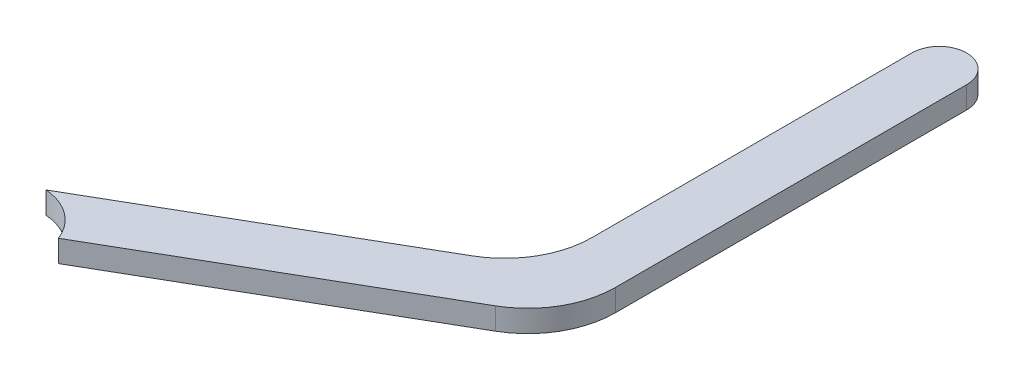
SolidWorks part; units mm, degrees
material "Acrylic (Medium-high impact)"
ref_plane "Front Plane" through (0, 0, 0) normal (0, 0, 1) x (1, 0, 0)
ref_plane "Top Plane" through (0, 0, 0) normal (0, 1, 0) x (1, 0, 0)
ref_plane "Right Plane" through (0, 0, 0) normal (1, 0, 0) x (0, 0, -1)
sketch "Sketch1" plane through (0, 0, 0) normal (0, 1, 0) x (1, 0, 0)
  line L0 (0, 0) -> (-94.8623, -54.7688) construction
  line L1 (0, 0) -> (0, 111.6203) construction
  line L3 (7.9375, 111.6203) -> (7.9375, -4.5827)
  line L4 (-90.8935, -61.6428) -> (7.9375, -4.5827)
  line L5 (-98.831, -47.8947) -> (-90.8935, -61.6428) construction
  line L6 (-98.831, -47.8947) -> (-7.9375, 4.5827)
  line L7 (-7.9375, 111.6203) -> (-7.9375, 4.5827)
  line L9 (-7.9375, 111.6203) -> (7.9375, 111.6203) construction
  arc A0 (-7.9375, 111.6203) -> (7.9375, 111.6203) centre (0, 111.6203) cw
  arc A2 (-98.831, -47.8947) -> (-90.8935, -61.6428) centre (-94.8623, -54.7688) ccw
  point P14 (-94.8623, -54.7688)
  point P18 (0, 0)
  point P22 (0, 111.6203)
  dimension "D1" = 111.6203
  dimension "D2" = 60
  dimension "D3" = 109.5375
  dimension "D4" = 15.875
extrude "Boss-Extrude1" add sketch "Sketch1" along normal blind 6.35
ref_plane "Plane1" through (0, 0, 0) normal (0.5, 0, 0.866) x (0.866, 0, -0.5)
sketch "Sketch2" plane through (0, 6.35, 0) normal (0, 1, 0) x (1, 0, 0)
  line L0 (-90.8935, -61.6428) -> (7.9375, -4.5827) construction
  line L1 (-84.9318, -58.2009) -> (0, -9.1654) construction
  line L2 (-98.831, -47.8947) -> (-15.875, 0) construction
  line L3 (-84.9318, -58.2009) -> (-90.8935, -61.6428)
  line L4 (-7.9375, 4.5827) -> (-98.831, -47.8947) construction
  line L5 (-90.8935, -61.6428) -> (7.9375, -4.5827) construction
  arc A1 (-98.831, -47.8947) -> (-90.8935, -61.6428) centre (-94.8623, -54.7688) ccw construction
  arc A2 (-98.831, -47.8947) -> (-84.9318, -58.2009) centre (-100.0343, -64.043) cw
  arc A3 (-98.831, -47.8947) -> (-90.8935, -61.6428) centre (-94.8623, -54.7688) ccw
  point P2 (-101.7363, -58.7375)
  line M4 (-90.8935, -61.6428) -> (7.9375, -4.5827)
  arc M11 (-98.831, -47.8947) -> (-90.8935, -61.6428) centre (-94.8623, -54.7688) ccw
  dimension "D1" = 16.1931
  dimension "D2" = 16.8045
extrude "Cut-Extrude1" cut sketch "Sketch2" against normal through all contours A2 M11 M4
fillet "Fillet1" radius 25.4 2 edges at (7.9375, 3.175, 4.5827) (-7.9375, 3.175, -4.5827)
sketch "Sketch3" plane through (0, 6.35, 0) normal (0, 1, 0) x (1, 0, 0)
  line L0 (0, 119.5578) -> (0, 0)
  line L1 (0, 0) -> (-94.8623, -54.7688)
  line L2 (-94.8623, -54.7688) -> (-98.831, -47.8947)
  line L3 (-20.6375, -2.7496) -> (-98.831, -47.8947) construction
  line L4 (-94.8623, -54.7688) -> (-90.8935, -61.6428)
  line L5 (-90.8935, -61.6428) -> (-84.9318, -58.2009)
  line L6 (5.8509, 0) -> (-16.7635, 0)
  line L7 (5.8509, 0) -> (-5.4563, 19.5846)
  arc A0 (7.9375, 111.6203) -> (-7.9375, 111.6203) centre (0, 111.6203) ccw construction
  arc A1 (-4.7625, -11.9151) -> (7.9375, 10.082) centre (-17.4625, 10.082) ccw construction
  arc A2 (-20.6375, -2.7496) -> (-7.9375, 19.2474) centre (-33.3375, 19.2474) ccw construction
ref_plane "Plane2" through (0, 0, -119.5578) normal (0, 0, -1) x (-1, 0, 0)
